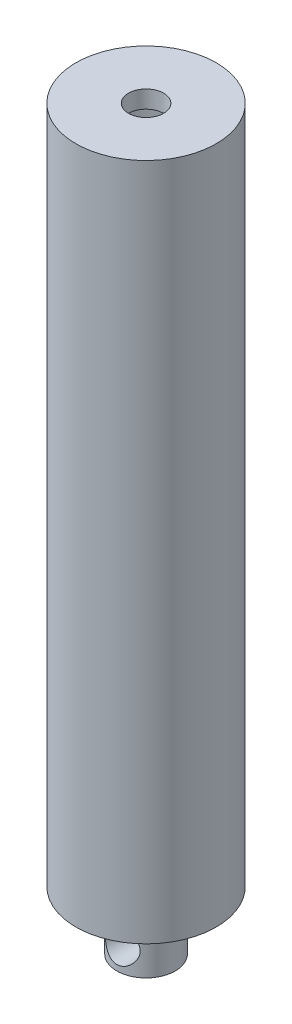
SolidWorks part; units mm, degrees
ref_plane "Front" through (0, 0, 0) normal (0, 0, 1) x (1, 0, 0)
ref_plane "Top" through (0, 0, 0) normal (0, 1, 0) x (1, 0, 0)
ref_plane "Right" through (0, 0, 0) normal (1, 0, 0) x (0, 0, -1)
sketch "草图1" plane through (0, 0, 0) normal (0, 0, 1) x (1, 0, 0)
  line L0 (0, 0) -> (0, 13.8214) construction
  line L1 (0, 0) -> (-5, 0)
  line L2 (-5, 0) -> (-5, 10)
  line L3 (-5, 10) -> (-12, 10)
  line L4 (-12, 10) -> (-12, 126)
  line L5 (-12, 126) -> (-3, 126)
  line L6 (-3, 126) -> (-3, 123)
  line L7 (-3, 123) -> (-10, 123)
  line L8 (-10, 123) -> (-10, 13)
  line L9 (-10, 13) -> (0, 13)
  line L10 (0, 13) -> (0, 0)
  dimension "D1" = 110
  dimension "D2" = 3
  dimension "D3" = 10
  dimension "D4" = 2
  dimension "D5" = 3
  dimension "D6" = 5
  dimension "D7" = 3
  dimension "D8" = 10
revolve "旋转1" add sketch "草图1" angle 360 about L0
sketch "草图2" plane through (0, 0, 0) normal (0, 0, 1) x (1, 0, 0)
  circle A0 centre (0, 3.9633) radius 3
  dimension "D1" = 6
extrude "切除-拉伸1" cut sketch "草图2" against normal through all both and the other way through all
